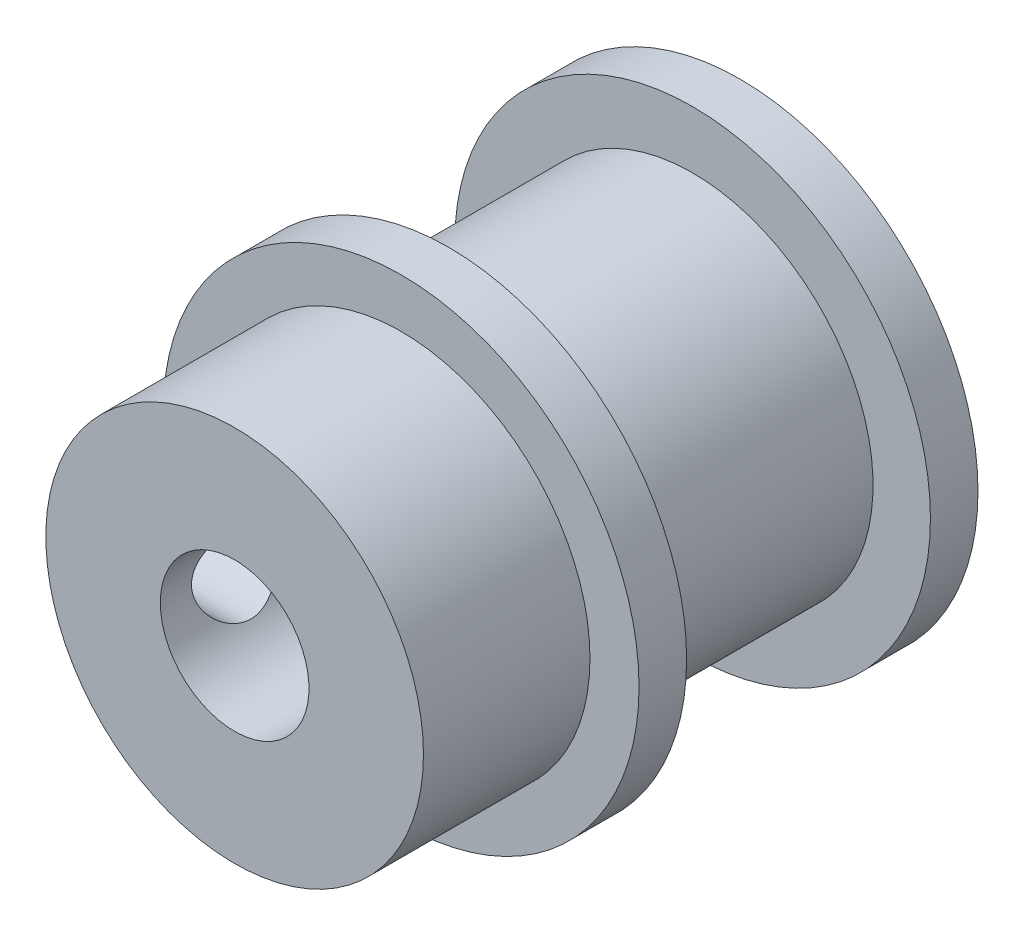
SolidWorks part; units mm, degrees
ref_plane "Front" through (0, 0, 0) normal (0, 0, 1) x (1, 0, 0)
ref_plane "Top" through (0, 0, 0) normal (0, 1, 0) x (1, 0, 0)
ref_plane "Right" through (0, 0, 0) normal (1, 0, 0) x (0, 0, -1)
sketch "Sketch1" plane through (0, 0, 0) normal (0, 1, 0) x (1, 0, 0)
  line L0 (8, -9.8) -> (0, -9.8)
  line L1 (0, -9.8) -> (0, -11.4)
  line L2 (0, -11.4) -> (8, -11.4)
  line L3 (8, -11.4) -> (8, -9.8)
  line L4 (0, -9.8) -> (0, -11.4) construction
  dimension "D1" = 8
  dimension "D2" = 1.6
revolve "Revolve1" add sketch "Sketch1" angle 360 about L4
sketch "Sketch2" plane through (0, 0, 9.8) normal (0, 0, -1) x (-1, 0, 0)
  circle A0 centre (0, 0) radius 6.07
  dimension "D1" = 12.14
extrude "Boss-Extrude1" add sketch "Sketch2" along normal blind 8.2
ref_plane "Plane1" through (0, 0, 1.6) normal (0, 0, 1) x (1, 0, 0)
sketch "Sketch3" plane through (0, 0, 1.6) normal (0, 0, 1) x (1, 0, 0)
  circle A0 centre (0, 0) radius 8
  dimension "D1" = 16
extrude "Boss-Extrude2" add sketch "Sketch3" against normal blind 1.6
sketch "Sketch4" plane through (0, 0, 11.4) normal (0, 0, 1) x (1, 0, 0)
  circle A0 centre (0, 0) radius 6.35
  dimension "D1" = 12.7
extrude "Boss-Extrude3" add sketch "Sketch4" along normal blind 5.6
hole_wizard "Ø5.0 (5) Diameter Hole1" positions "Sketch6" profile "Sketch5" hole size "Ø5.0" standard "ANSI Metric"
sketch "Sketch6" plane through (0, 0, 0) normal (0, 0, -1) x (-1, 0, 0)
  point P0 (0, 0)
sketch "Sketch5" plane through (0, 0, 0) normal (1, 0, 0) x (0, 1, 0)
  line L0 (0, 0) -> (0, 17)
  line L1 (0, 17) -> (2.5, 17)
  line L2 (2.5, 17) -> (2.5, 0)
  line L5 (2.5, 0) -> (0, 0)
  line L11 (0, -6.35) -> (0, 107.95) construction
  dimension "Thru Hole Dia." = 5
  dimension "Thru Hole Depth" = 17
hole_wizard "Ø3.0 (3) Diameter Hole1" positions "3DSketch1" profile "Sketch7" hole size "Ø3.0" standard "ANSI Metric"
sketch3d "3DSketch1"
  point P0 (-6.35, 0, 14.4528)
sketch "Sketch7" plane through (-6.35, 0, 14.4528) normal (0, 1, 0) x (0, 0, 1)
  line L0 (0, 0) -> (0, 3.85)
  line L1 (0, 3.85) -> (1.5, 3.85)
  line L2 (1.5, 3.85) -> (1.5, 0)
  line L5 (1.5, 0) -> (0, 0)
  line L11 (0, -6.35) -> (0, 107.95) construction
  dimension "Thru Hole Dia." = 3
  dimension "Thru Hole Depth" = 3.85
